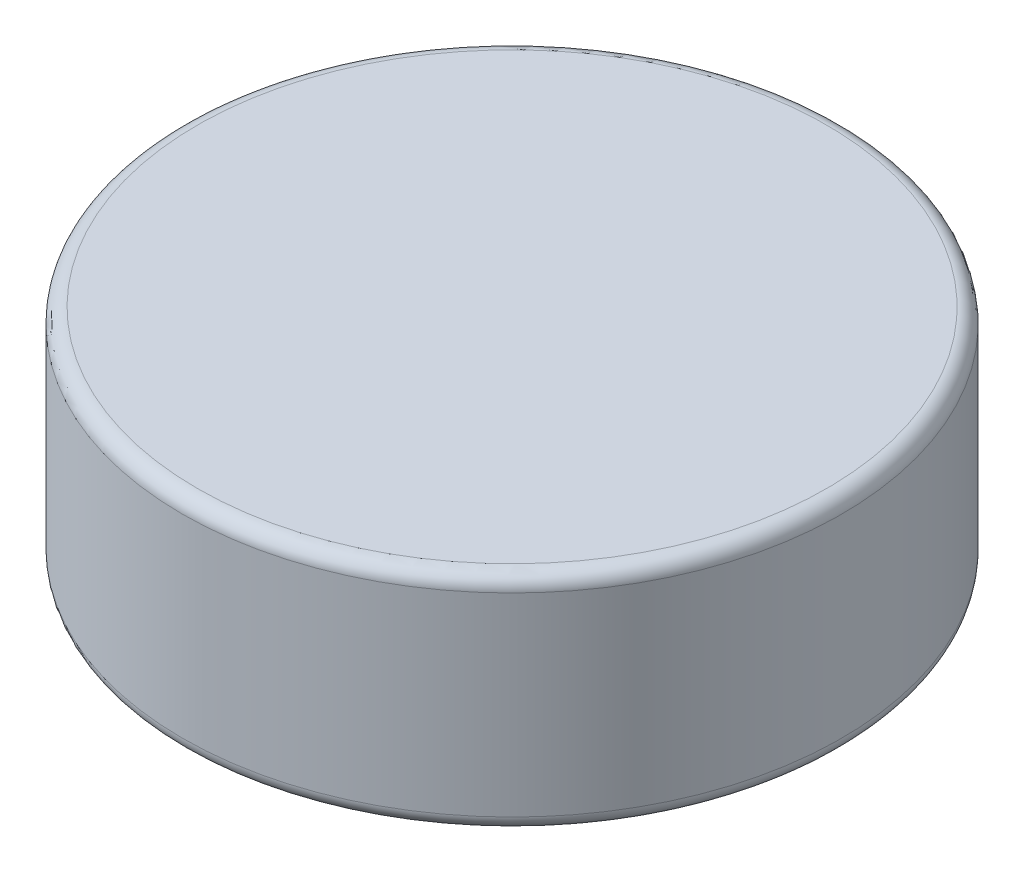
SolidWorks part; units mm, degrees
ref_plane "Front" through (0, 0, 0) normal (0, 0, 1) x (1, 0, 0)
ref_plane "Top" through (0, 0, 0) normal (0, 1, 0) x (1, 0, 0)
ref_plane "Right" through (0, 0, 0) normal (1, 0, 0) x (0, 0, -1)
sketch "Sketch2" plane through (0, 0, 0) normal (0, 1, 0) x (1, 0, 0)
  circle A0 centre (0, 0) radius 22.1869
  dimension "D1" = 44.3738
extrude "Boss-Extrude1" add sketch "Sketch2" along normal blind 15.0622
fillet "Fillet1" radius 1 2 edges at (0, 0, 22.1869) (0, 15.0622, 22.1869)
